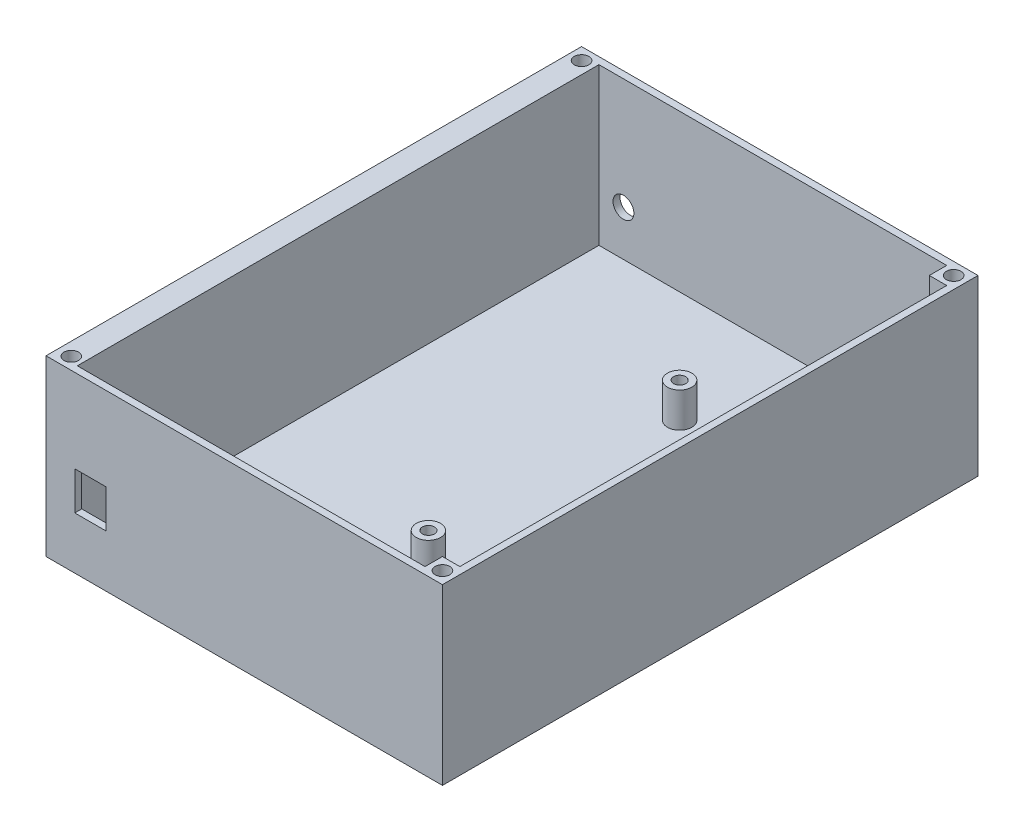
SolidWorks part; units mm, degrees
ref_plane "Front Plane" through (0, 0, 0) normal (0, 0, 1) x (1, 0, 0)
ref_plane "Top Plane" through (0, 0, 0) normal (0, 1, 0) x (1, 0, 0)
ref_plane "Right Plane" through (0, 0, 0) normal (1, 0, 0) x (0, 0, -1)
sketch "Sketch3" plane through (0, 0, 0) normal (0, 1, 0) x (1, 0, 0)
  line L1 (-57, -82) -> (57, -82)
  line L2 (-57, -82) -> (-57, 82)
  line L3 (-57, 82) -> (57, 82)
  line L4 (57, -82) -> (57, 82)
  line L5 (-57, -82) -> (57, 82) construction
  line L6 (-57, 82) -> (57, -82) construction
  point P0 (0, 0)
  dimension "D1" = 114
  dimension "D2" = 164
extrude "Boss-Extrude2" add sketch "Sketch3" along normal blind 50
sketch "Sketch4" plane through (0, 50, 0) normal (0, 1, 0) x (1, 0, 0)
  line L1 (50, 75) -> (-50, 75)
  line L2 (50, 75) -> (50, -75)
  line L3 (50, -75) -> (-50, -75)
  line L4 (-50, 75) -> (-50, -75)
  line L5 (50, 75) -> (-50, -75) construction
  line L6 (50, -75) -> (-50, 75) construction
  point P0 (0, 0)
  dimension "D1" = 100
  dimension "D2" = 150
extrude "Cut-Extrude2" cut sketch "Sketch4" against normal blind 45
sketch "Sketch8" plane through (0, 0, 75) normal (0, 0, -1) x (-1, 0, 0)
  line L0 (50, 5) -> (-50, 5) construction
  line L1 (50, 5) -> (50, 50) construction
  line L3 (48.8, 5) -> (39.8, 5)
  line L4 (48.8, 5) -> (48.8, 16)
  line L5 (48.8, 16) -> (39.8, 16)
  line L6 (39.8, 5) -> (39.8, 16)
  point P0 (48.8, 5)
  dimension "D1" = 1.2
  dimension "D2" = 11
  dimension "D3" = 9
sketch "Sketch9" plane through (0, 50, 0) normal (0, 1, 0) x (1, 0, 0)
  line L0 (57, -82) -> (57, 82) construction
  line L1 (-57, -82) -> (57, -82)
  line L2 (-57, -82) -> (-57, -77)
  line L3 (-57, -77) -> (57, -77)
  line L4 (57, -82) -> (57, -77)
  dimension "D1" = 5
  dimension "D2" = 114
extrude "Cut-Extrude5" cut sketch "Sketch9" against normal through all
sketch "Sketch10" plane through (0, 50, 0) normal (0, 1, 0) x (1, 0, 0)
  line L0 (57, -77) -> (57, 82) construction
  line L1 (-57, 82) -> (57, 82)
  line L2 (-57, 82) -> (-57, 77)
  line L3 (-57, 77) -> (57, 77)
  line L4 (57, 82) -> (57, 77)
  dimension "D1" = 5
extrude "Cut-Extrude6" cut sketch "Sketch10" against normal through all
sketch "Sketch11" plane through (0, 0, -75) normal (0, 0, 1) x (1, 0, 0)
  line L0 (50, 5) -> (-50, 5) construction
  circle A0 centre (42.25, 8) radius 3
  circle A1 centre (-42.95, 8) radius 3
  point P0 (-42.95, 5)
  point P1 (42.25, 5)
  point P4 (-42.95, 8)
  point P7 (42.25, 8)
  dimension "D5" = 6
  dimension "D6" = 6
  dimension "D1" = 7.75
  dimension "D2" = 7.05
  dimension "D3" = 3
  dimension "D4" = 3
sketch "Sketch12" plane through (0, 50, 0) normal (0, 1, 0) x (1, 0, 0)
  line L0 (57, -77) -> (-57, -77) construction
  line L1 (-57, 77) -> (-57, -77) construction
  circle A0 centre (-53.2365, -73.5) radius 2.1
  point P0 (-53.5, -77)
  point P5 (-57, -73.5)
  point P6 (-53.5, -73.5)
  dimension "D3" = 4.2
  dimension "D1" = 3.5
  dimension "D2" = 3.5
extrude "Cut-Extrude8" cut sketch "Sketch12" against normal blind 20
sketch "Sketch13" plane through (0, 50, 0) normal (0, 1, 0) x (1, 0, 0)
  line L0 (57, -77) -> (57, 77) construction
  line L1 (57, -77) -> (-57, -77) construction
  circle A0 centre (53.5, -73.5) radius 2.1
  point P0 (57, -73.5)
  point P1 (53.5, -77)
  point P4 (53.5, -73.5)
  dimension "D3" = 4.2
  dimension "D1" = 3.5
  dimension "D2" = 3.5
extrude "Cut-Extrude9" cut sketch "Sketch13" against normal blind 20
sketch "Sketch14" plane through (0, 50, 0) normal (0, 1, 0) x (1, 0, 0)
  line L0 (-57, 77) -> (57, 77) construction
  line L1 (57, -77) -> (57, 77) construction
  line L2 (-57, 77) -> (-57, -77) construction
  circle A0 centre (53.5, 73.5) radius 2.1
  circle A1 centre (-53.5, 73.5) radius 2.1
  point P0 (53.5, 77)
  point P1 (57, 73.5)
  point P4 (53.5, 73.5)
  point P10 (-57, 73.5)
  point P11 (-53.5, 77)
  point P14 (-53.5, 73.5)
  dimension "D3" = 4.2
  dimension "D6" = 4.2
  dimension "D1" = 3.5
  dimension "D2" = 3.5
  dimension "D4" = 3.5
  dimension "D5" = 3.5
extrude "Cut-Extrude10" cut sketch "Sketch14" against normal blind 20
sketch "Sketch15" plane through (0, 50, 0) normal (0, 1, 0) x (1, 0, 0)
  line L0 (50, -75) -> (50, 75) construction
  line L1 (-57, 77) -> (57, 77) construction
  line L2 (57, -77) -> (-57, -77) construction
  line L4 (50, 70) -> (55, 70)
  line L5 (50, 70) -> (50, -70)
  line L6 (50, -70) -> (55, -70)
  line L7 (55, 70) -> (55, -70)
  point P0 (50, 70)
  point P5 (50, -70)
  dimension "D1" = 7
  dimension "D2" = 7
  dimension "D3" = 5
extrude "Cut-Extrude11" cut sketch "Sketch15" against normal blind 45
sketch "Sketch16" plane through (0, 5, 0) normal (0, 1, 0) x (1, 0, 0)
  circle A0 centre (5.1729, 43.031) radius 3.5
  circle A1 centre (6.476, -30.5097) radius 3.5
  dimension "D1" = 7
  dimension "D2" = 7
extrude "Boss-Extrude3" add sketch "Sketch16" along normal blind 10
sketch "Sketch17" plane through (0, 15, 0) normal (0, 1, 0) x (1, 0, 0)
  circle A0 centre (5.1729, 43.031) radius 1.75
  dimension "D1" = 3.5
extrude "Cut-Extrude12" cut sketch "Sketch17" against normal blind 8
sketch "Sketch18" plane through (0, 15, 0) normal (0, 1, 0) x (1, 0, 0)
  circle A0 centre (6.476, -30.5097) radius 1.75
  dimension "D1" = 3.5
extrude "Cut-Extrude13" cut sketch "Sketch18" against normal blind 8
sketch "Sketch19" plane through (0, 0, 75) normal (0, 0, -1) x (-1, 0, 0)
  line L1 (48.7227, 15) -> (39.7227, 15)
  line L2 (48.7227, 15) -> (48.7227, 26)
  line L3 (48.7227, 26) -> (39.7227, 26)
  line L4 (39.7227, 15) -> (39.7227, 26)
  point P0 (48.7227, 15)
  dimension "D1" = 10
  dimension "D2" = 11
  dimension "D3" = 9
extrude "Cut-Extrude14" cut sketch "Sketch19" against normal through all
sketch "Sketch21" plane through (0, 0, -75) normal (0, 0, 1) x (1, 0, 0)
  line L0 (42.25, 5) -> (42.25, 18)
  circle A0 centre (42.25, 18) radius 3
  dimension "D2" = 6
  dimension "D1" = 13
extrude "Cut-Extrude16" cut sketch "Sketch21" against normal through all
sketch "Sketch22" plane through (0, 0, -75) normal (0, 0, 1) x (1, 0, 0)
  line L0 (-42.95, 5) -> (-42.95, 18)
  circle A0 centre (-42.95, 18) radius 3
  dimension "D2" = 6
  dimension "D1" = 13
extrude "Cut-Extrude17" cut sketch "Sketch22" against normal through all
